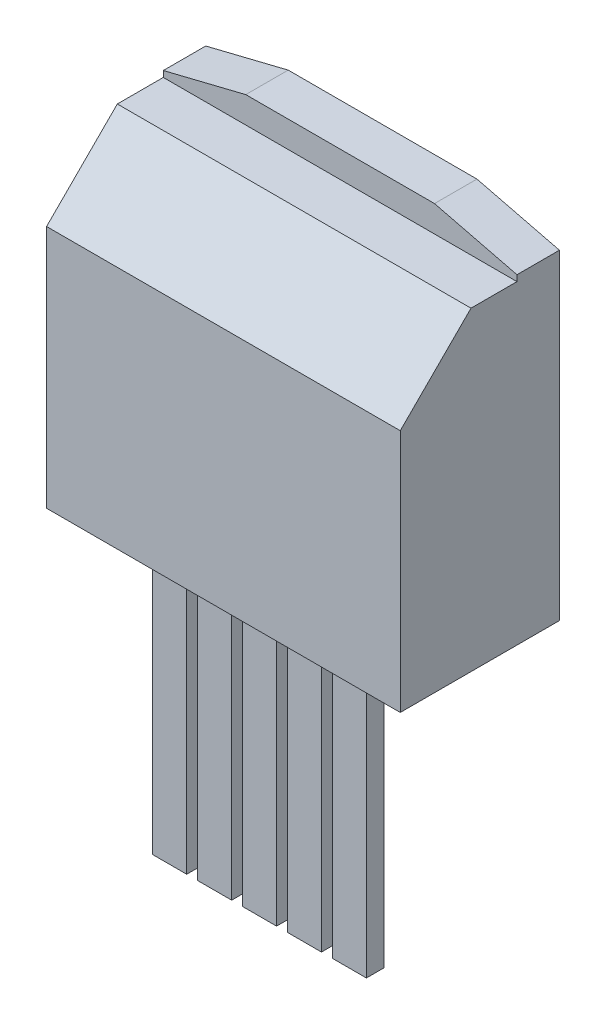
SolidWorks part; units mm, degrees
ref_plane "前视基准面" through (0, 0, 0) normal (0, 0, 1) x (1, 0, 0)
ref_plane "上视基准面" through (0, 0, 0) normal (0, 1, 0) x (1, 0, 0)
ref_plane "右视基准面" through (0, 0, 0) normal (1, 0, 0) x (0, 0, -1)
sketch "草图1" plane through (0, 0, 0) normal (0, 0, 1) x (1, 0, 0)
  line L0 (0, 13.5549) -> (0, -16.5771) construction
  line L1 (-5, 15.4) -> (5, 15.4)
  line L2 (-5, 15.4) -> (-5, 0)
  line L3 (-5, 0) -> (5, 0)
  line L4 (5, 15.4) -> (5, 0)
  line L5 (-12.7598, 0) -> (15.1062, 0) construction
  dimension "D1" = 15.4
  dimension "D2" = 10
extrude "凸台-拉伸1" add sketch "草图1" along normal blind 4.5
sketch "草图2" plane through (0, 0, 4.5) normal (0, 0, 1) x (1, 0, 0)
  line L0 (5, 0) -> (5, 15.4) construction
  line L1 (-5, 15.4) -> (5, 15.4)
  line L2 (-5, 15.4) -> (-5, 8.9)
  line L3 (-5, 8.9) -> (5, 8.9)
  line L4 (5, 15.4) -> (5, 8.9)
  dimension "D1" = 6.5
extrude "切除-拉伸1" cut sketch "草图2" against normal offset from surface (3.3 mm away) 1.2 up to face at (0, 7.7, 0)
chamfer "倒角1" distance 2 angle 45 1 edges at (0, 8.9, 4.5)
sketch "草图5" plane through (0, 0, 1.2) normal (0, 0, 1) x (1, 0, 0)
  line L0 (0, -1.1784) -> (0, 16.9104) construction
  line L1 (-5, 9.0696) -> (-2.668, 9.6454)
  line L2 (-5, 8.9) -> (-5, 15.4) construction
  line L3 (-2.668, 9.6454) -> (2.668, 9.6454)
  line L4 (5, 9.0696) -> (2.668, 9.6454)
  line L5 (-5, 9.0696) -> (-5, 15.4)
  line L6 (-5, 15.4) -> (5, 15.4)
  line L7 (5, 15.4) -> (5, 9.0696)
  point P9 (0, 9.6454)
extrude "切除-拉伸2" cut sketch "草图5" against normal blind 10
sketch "草图4" plane through (0, 0, 0) normal (0, -1, 0) x (1, 0, 0)
  line L0 (0, -1.662) -> (0, 5.2997) construction
  line L1 (-5.719, 3.23) -> (6.0741, 3.23) construction
  line L2 (-5, 4.5) -> (5, 4.5) construction
  line L3 (0.7872, 3.48) -> (1.7528, 3.48)
  line L4 (-0.4828, 3.48) -> (0.4828, 3.48)
  line L5 (-0.4828, 3.48) -> (-0.4828, 2.98)
  line L6 (-0.4828, 2.98) -> (0.4828, 2.98)
  line L7 (0.4828, 3.48) -> (0.4828, 2.98)
  line L8 (0.7872, 3.48) -> (0.7872, 2.98)
  line L9 (0.7872, 2.98) -> (1.7528, 2.98)
  line L10 (1.7528, 3.48) -> (1.7528, 2.98)
  line L11 (-1.7528, 3.48) -> (-0.7872, 3.48)
  line L12 (-1.7528, 3.48) -> (-1.7528, 2.98)
  line L13 (-1.7528, 2.98) -> (-0.7872, 2.98)
  line L14 (-0.7872, 3.48) -> (-0.7872, 2.98)
  line L15 (-3.0228, 3.48) -> (-2.0572, 3.48)
  line L16 (-3.0228, 3.48) -> (-3.0228, 2.98)
  line L17 (-3.0228, 2.98) -> (-2.0572, 2.98)
  line L18 (-2.0572, 3.48) -> (-2.0572, 2.98)
  line L19 (2.0572, 3.48) -> (3.0228, 3.48)
  line L20 (2.0572, 3.48) -> (2.0572, 2.98)
  line L21 (2.0572, 2.98) -> (3.0228, 2.98)
  line L22 (3.0228, 3.48) -> (3.0228, 2.98)
  dimension "D1" = 1.27
  dimension "D2" = 0.9656
  dimension "D3" = 0.5
  dimension "D4" = 3
  dimension "D5" = 3
extrude "凸台-拉伸2" add sketch "草图4" along normal blind 8
